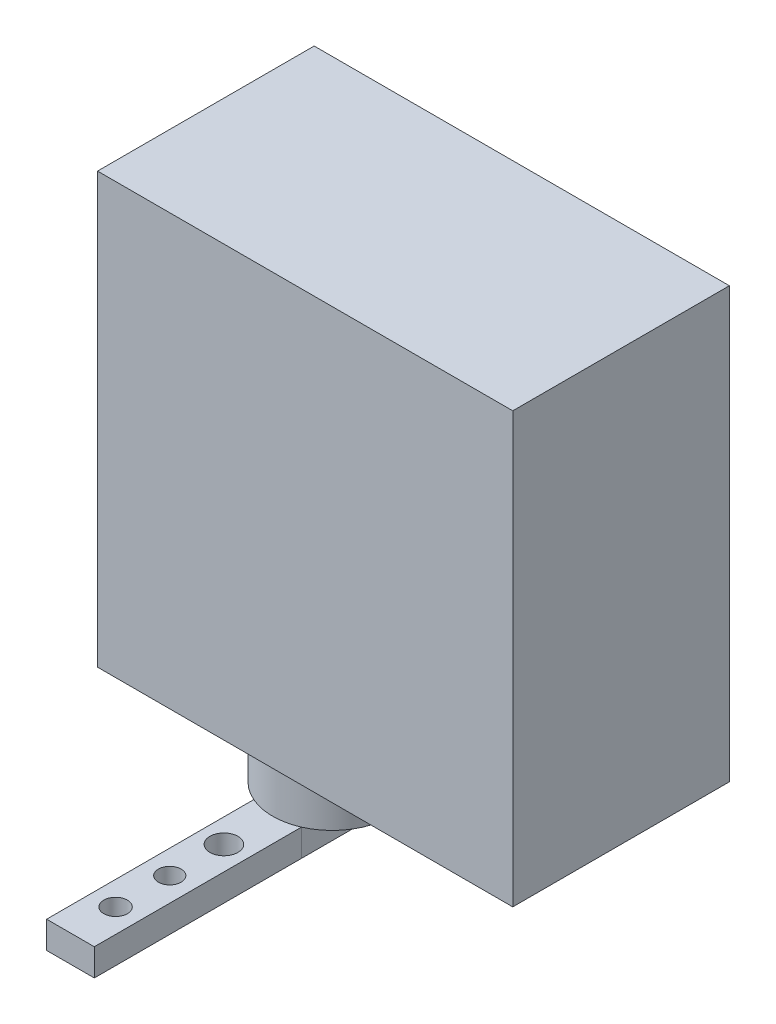
SolidWorks part; units mm, degrees
ref_plane "Front Plane" through (0, 0, 0) normal (0, 0, 1) x (1, 0, 0)
ref_plane "Top Plane" through (0, 0, 0) normal (0, 1, 0) x (1, 0, 0)
ref_plane "Right Plane" through (0, 0, 0) normal (1, 0, 0) x (0, 0, -1)
sketch "Sketch1" plane through (0, 0, 0) normal (0, 1, 0) x (1, 0, 0)
  line L1 (0, 0) -> (23, 0)
  line L2 (0, 0) -> (0, 12)
  line L3 (0, 12) -> (23, 12)
  line L4 (23, 0) -> (23, 12)
  dimension "D1" = 23
  dimension "D2" = 12
extrude "Boss-Extrude1" add sketch "Sketch1" along normal blind 23.8
sketch "Sketch2" plane through (0, 0, 0) normal (0, -1, 0) x (1, 0, 0)
  line L0 (0, 0) -> (23, 0) construction
  line L1 (0, -12) -> (0, 0) construction
  circle A0 centre (7, -6) radius 3.3
  dimension "D1" = 6
  dimension "D2" = 7
extrude "Boss-Extrude2" add sketch "Sketch2" along normal blind 5
sketch "Sketch3" plane through (0, -5, 0) normal (0, -1, 0) x (1, 0, 0)
  line L0 (5.679, -6) -> (8.321, -6)
  line L1 (5.679, -20.5) -> (8.321, -20.5)
  line L2 (5.679, -20.5) -> (5.679, 8.5)
  line L3 (5.679, 8.5) -> (8.321, 8.5)
  line L4 (8.321, -20.5) -> (8.321, 8.5)
  line L5 (5.679, -20.5) -> (8.321, 8.5) construction
  line L6 (5.679, 8.5) -> (8.321, -20.5) construction
  arc A1 (8.321, -2.974) -> (5.679, -2.974) centre (7, -6) ccw
  circle A2 centre (7, -6) radius 3.3 construction
  arc A3 (5.679, -9.026) -> (8.321, -9.026) centre (7, -6) ccw
  circle A4 centre (7, 0) radius 0.7756
  circle A5 centre (7, 3) radius 0.6312
  circle A6 centre (7, 6) radius 0.6545
  circle A7 centre (7, -18) radius 0.6545
  circle A8 centre (7, -15) radius 0.6312
  circle A9 centre (7, -12) radius 0.7756
  circle M8 centre (7, -6) radius 3.3
  dimension "D1" = 29
  dimension "D2" = 0
  dimension "D3" = 6
  dimension "D4" = 9
  dimension "D5" = 12
extrude "Boss-Extrude3" add sketch "Sketch3" along normal blind 1.5 contours A1 L4 L3 L2 A6 A5 A4 | L0 L4 L2 M8 | L4 L0 L2 M8 | A3 L2 L1 L4 A8 A7 A9
